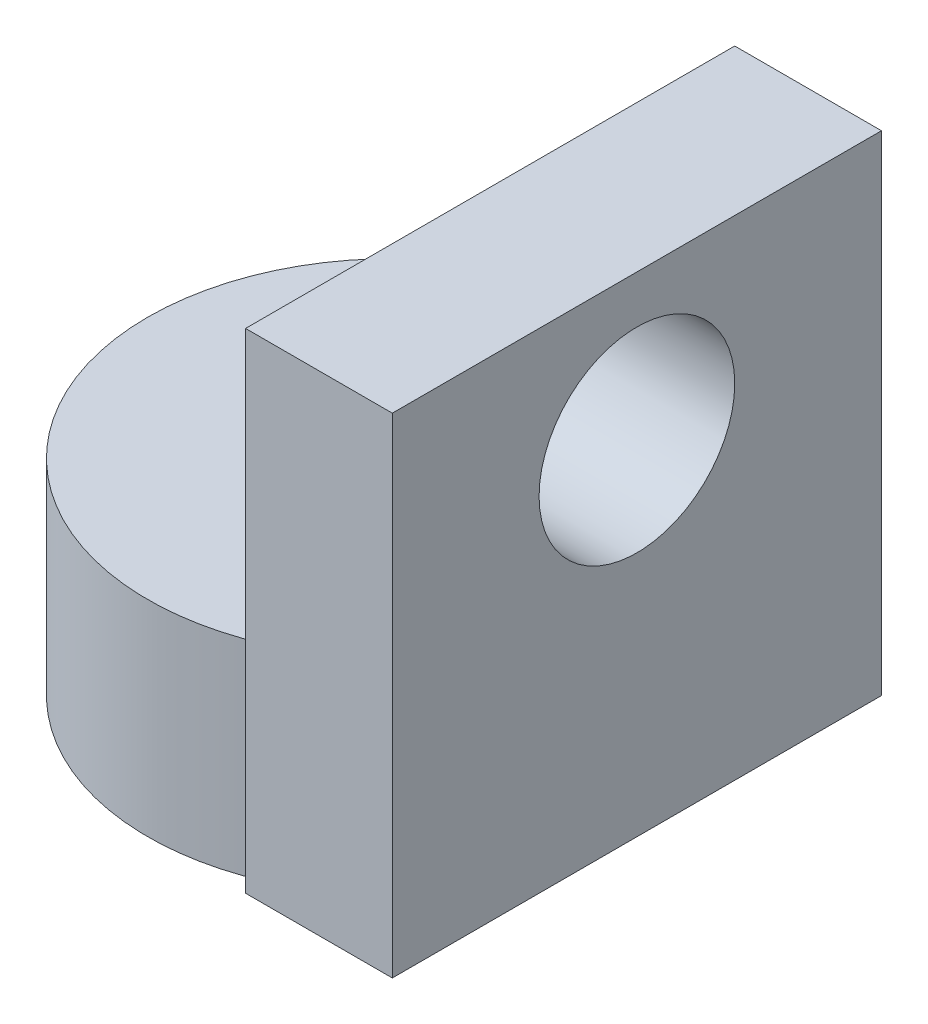
SolidWorks part; units mm, degrees
ref_plane "Front Plane" through (0, 0, 0) normal (0, 0, 1) x (1, 0, 0)
ref_plane "Top Plane" through (0, 0, 0) normal (0, 1, 0) x (1, 0, 0)
ref_plane "Right Plane" through (0, 0, 0) normal (1, 0, 0) x (0, 0, -1)
sketch "Sketch1" plane through (0, 0, 0) normal (0, 1, 0) x (1, 0, 0)
  circle A0 centre (0, 0) radius 1
  circle A1 centre (0, 0) radius 2.5
  dimension "D1" = 2
  dimension "D2" = 5
extrude "Boss-Extrude2" add sketch "Sketch1" along normal blind 2.1
ref_plane "Plane1" through (2.5, 0, 0) normal (1, 0, 0) x (0, 0, -1)
sketch "Sketch2" plane through (2.5, 0, 0) normal (1, 0, 0) x (0, 0, -1)
  line L1 (-2.5, 0) -> (2.5, 0)
  line L2 (-2.5, 0) -> (-2.5, 5)
  line L3 (-2.5, 5) -> (2.5, 5)
  line L4 (2.5, 0) -> (2.5, 5)
  circle A0 centre (0, 3.5131) radius 1
  dimension "D3" = 2
  dimension "D1" = 5
  dimension "D2" = 5
extrude "Boss-Extrude3" add sketch "Sketch2" against normal blind 1.5
